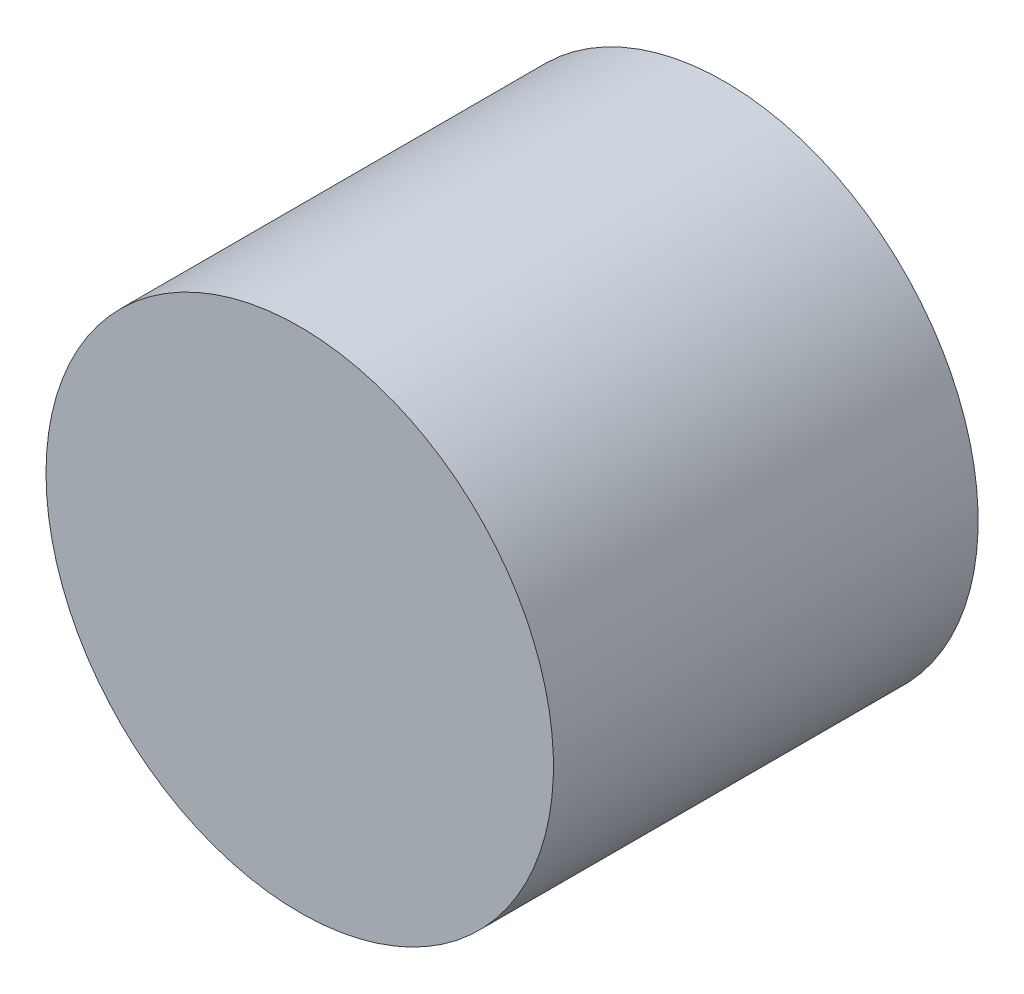
SolidWorks part; units mm, degrees
material "Rubber"
ref_plane "Plane1" through (0, 0, 0) normal (0, 0, 1) x (1, 0, 0)
ref_plane "Plane2" through (0, 0, 0) normal (0, 1, 0) x (1, 0, 0)
ref_plane "Plane3" through (0, 0, 0) normal (1, 0, 0) x (0, 0, -1)
other "Configuration Table"
sketch "Sketch1" plane through (0, 0, 0) normal (0, 0, 1) x (1, 0, 0)
  circle A2 centre (-0.7394, 0.6843) radius 4.6
extrude "rubber feet" add sketch "Sketch1" along normal blind 7.7
equation "\"result\"= 0.000512"
equation "\"result\"= 5*1"
equation "\"result\"= 5.000000*0.950000"
